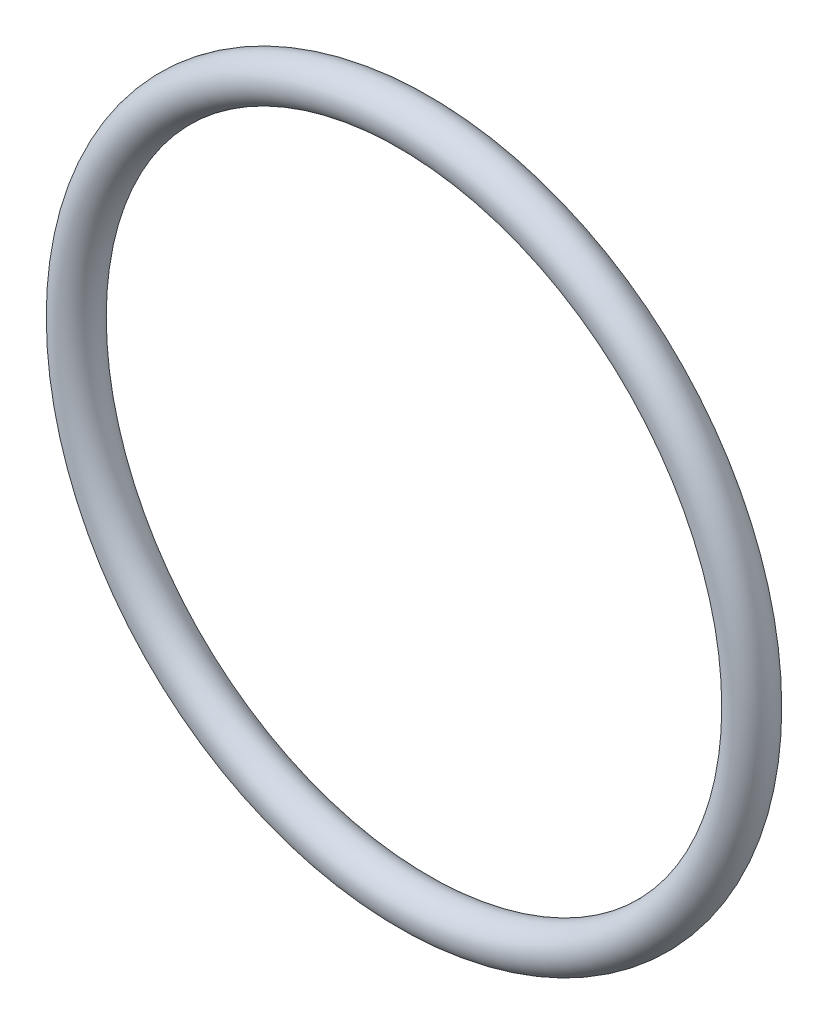
SolidWorks part; units mm, degrees
ref_plane "Front Plane" through (0, 0, 0) normal (0, 0, 1) x (1, 0, 0)
ref_plane "Top Plane" through (0, 0, 0) normal (0, 1, 0) x (1, 0, 0)
ref_plane "Right Plane" through (0, 0, 0) normal (1, 0, 0) x (0, 0, -1)
sketch "Sketch2" plane through (0, 0, 0) normal (0, 0, 1) x (1, 0, 0)
  circle A0 centre (14.0283, 0) radius 31.831
  dimension "D1" = 63.662
sketch "Sketch3" plane through (0, 0, 0) normal (0, 1, 0) x (1, 0, 0)
  line L0 (-17.8027, 0) -> (45.8593, 0) construction
  circle A0 centre (-17.8027, 0) radius 2
  dimension "D1" = 4
sweep "Sweep1" add profiles "Sketch3" path "Sketch2"
